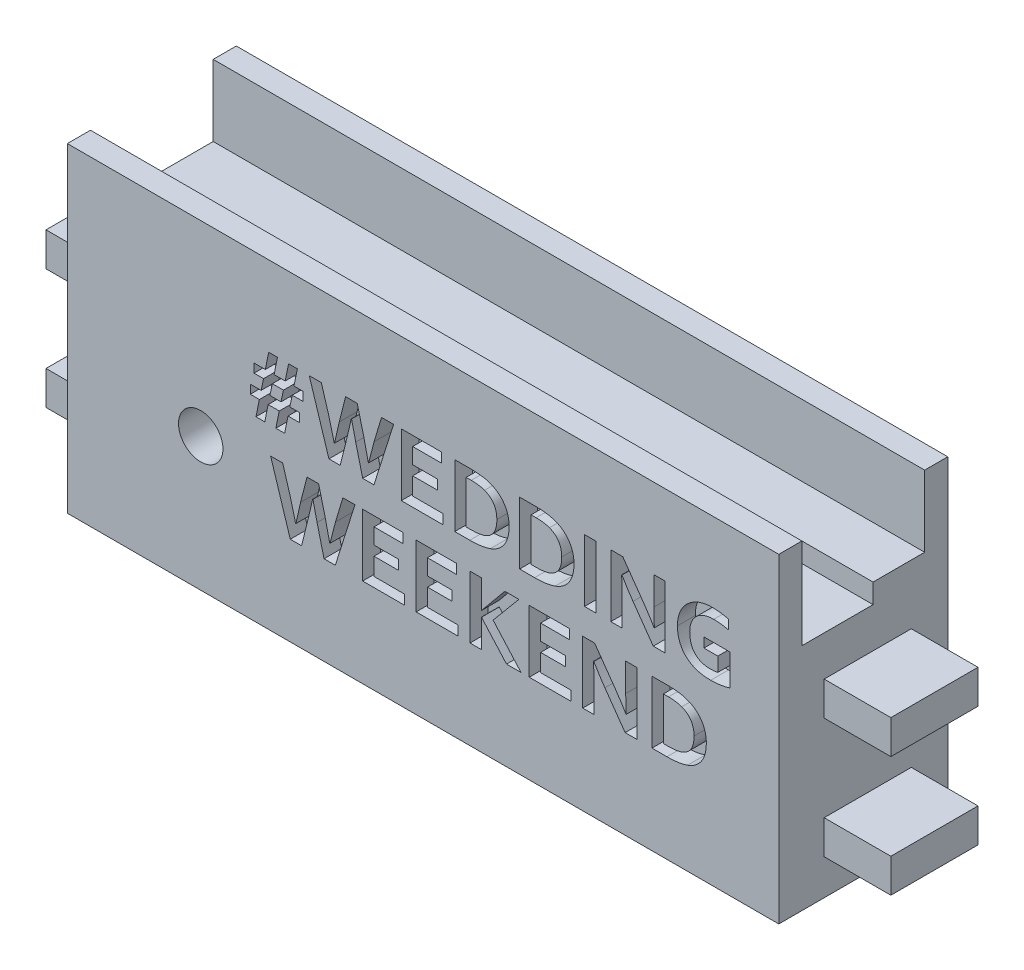
SolidWorks part; units mm, degrees
material "Copper"
ref_plane "Front Plane" through (0, 0, 0) normal (0, 0, 1) x (1, 0, 0)
ref_plane "Top Plane" through (0, 0, 0) normal (0, 1, 0) x (1, 0, 0)
ref_plane "Right Plane" through (0, 0, 0) normal (1, 0, 0) x (0, 0, -1)
sketch "Sketch1" plane through (0, 0, 0) normal (0, 0, 1) x (1, 0, 0)
  line L13 (0, 0) -> (101.6, 0)
  line L14 (0, 0) -> (0, 35.56)
  line L15 (0, 35.56) -> (101.6, 35.56)
  line L16 (101.6, 0) -> (101.6, 35.56)
  dimension "D1" = 35.56
  dimension "D2" = 101.6
extrude "Base Extrude" add sketch "Sketch1" along normal blind 24.13 contours L15 L16 L13 L14
sketch "Sketch2" plane through (101.6, 0, 0) normal (1, 0, 0) x (0, 0, -1)
  line L5 (-24.13, 0) -> (-24.13, 35.56) construction
  line L6 (-24.13, 35.56) -> (0, 35.56) construction
  line L14 (-11.43, 35.56) -> (-11.43, 0) construction
  line L15 (-24.13, 0) -> (0, 0) construction
  line L17 (-17.653, 9.906) -> (-5.207, 9.906)
  line L18 (-17.653, 9.906) -> (-17.653, 5.08)
  line L19 (-17.653, 5.08) -> (-5.207, 5.08)
  line L20 (-5.207, 9.906) -> (-5.207, 5.08)
  line L21 (-17.653, 27.051) -> (-5.207, 27.051)
  line L22 (-17.653, 27.051) -> (-17.653, 22.225)
  line L23 (-17.653, 22.225) -> (-5.207, 22.225)
  line L24 (-5.207, 27.051) -> (-5.207, 22.225)
  dimension "D1" = 12.7
  dimension "D2" = 22.225
  dimension "D4" = 12.446
  dimension "D5" = 4.826
  dimension "D6" = 5.08
  dimension "D8" = 6.223
extrude "Peg Extrude" add sketch "Sketch2" along normal blind 9.525
ref_plane "Peg Mirror Plane" through (50.8, 0, 0) normal (1, 0, 0) x (0, 0, -1)
mirror "Peg Mirror" about plane through (50.8, 0, 0) normal (1, 0, 0) of "Peg Extrude"
sketch "Sketch3" plane through (0, 35.56, 0) normal (0, 1, 0) x (1, 0, 0)
  line L0 (101.6, -24.13) -> (101.6, 0) construction
  line L1 (101.6, -24.13) -> (0, -24.13)
  line L2 (101.6, -24.13) -> (101.6, -20.828)
  line L3 (101.6, -20.828) -> (0, -20.828)
  line L4 (0, -24.13) -> (0, -20.828)
  line L5 (0, -24.13) -> (101.6, -24.13) construction
  line L6 (0, -24.13) -> (0, 0) construction
  line L8 (101.6, 0) -> (0, 0)
  line L9 (101.6, 0) -> (101.6, -3.302)
  line L10 (101.6, -3.302) -> (0, -3.302)
  line L11 (0, 0) -> (0, -3.302)
  dimension "D1" = 17.526
extrude "Picture Extrude" add sketch "Sketch3" along normal blind 10.16
sketch "Sketch6" plane through (0, 0, 0) normal (0, 0, -1) x (-1, 0, 0)
  line L0 (0, 0) -> (-101.6, 0) construction
  line L1 (-88.9, 31.115) -> (-31.75, 31.115)
  line L2 (-88.9, 31.115) -> (-88.9, 3.175)
  line L3 (-88.9, 3.175) -> (-31.75, 3.175)
  line L4 (-31.75, 31.115) -> (-31.75, 3.175)
  line L5 (-101.6, 0) -> (-101.6, 45.72) construction
  line L7 (-25.4, 31.115) -> (-12.7, 31.115)
  line L8 (-25.4, 31.115) -> (-25.4, 3.175)
  line L9 (-25.4, 3.175) -> (-12.7, 3.175)
  line L10 (-12.7, 31.115) -> (-12.7, 3.175)
  dimension "D1" = 57.15
  dimension "D2" = 27.94
  dimension "D3" = 3.175
  dimension "D4" = 12.7
  dimension "D5" = 12.7
  dimension "D6" = 6.35
  dimension "D7" = 27.94
extrude "Electronics Cut" cut sketch "Sketch6" against normal blind 19.05
sketch "Sketch7" plane through (31.75, 0, 0) normal (1, 0, 0) x (0, 0, -1)
  line L0 (-19.05, 3.175) -> (0, 3.175) construction
  line L1 (-6.35, 31.115) -> (0, 31.115)
  line L2 (-6.35, 31.115) -> (-6.35, 3.175)
  line L3 (-6.35, 3.175) -> (0, 3.175)
  line L4 (0, 31.115) -> (0, 3.175)
  line L5 (-19.05, 31.115) -> (0, 31.115) construction
  line L6 (0, 3.175) -> (0, 31.115) construction
  dimension "D1" = 6.35
extrude "Battery Wire Cut" cut sketch "Sketch7" against normal blind 6.35
sketch "Sketch8" plane through (0, 0, 19.05) normal (0, 0, -1) x (-1, 0, 0)
  line L1 (-88.9, 3.175) -> (-31.75, 3.175) construction
  line L2 (-25.4, 3.175) -> (-25.4, 31.115) construction
  circle A0 centre (-19.05, 19.05) radius 3.175
  dimension "D1" = 6.35
  dimension "D2" = 6.35
  dimension "D3" = 15.875
extrude "Switch Cut" cut sketch "Sketch8" against normal up to next
sketch "Sketch9" plane through (0, 35.56, 0) normal (0, 1, 0) x (1, 0, 0)
  line L1 (8.89, -14.478) -> (12.7, -14.478)
  line L2 (8.89, -14.478) -> (8.89, -20.828)
  line L3 (8.89, -20.828) -> (12.7, -20.828)
  line L4 (12.7, -14.478) -> (12.7, -20.828)
  line L5 (0, -20.828) -> (0, -3.302) construction
  line L7 (101.6, -20.828) -> (0, -20.828) construction
  point P4 (0, 0)
  point P8 (0, 0)
  dimension "D1" = 6.35
  dimension "D2" = 3.81
  dimension "D3" = 8.89
extrude "LED Wire Cut" cut sketch "Sketch9" against normal blind 12.7
sketch "Sketch10" plane through (0, 0, 0) normal (0, 0, -1) x (-1, 0, 0)
  line L1 (-101.6, 22.86) -> (0, 22.86) construction
  line L2 (-101.6, 0) -> (-101.6, 45.72) construction
  line L3 (0, 0) -> (0, 45.72) construction
  line L4 (-50.8, 45.72) -> (-50.8, 0) construction
  line L5 (-101.6, 45.72) -> (0, 45.72) construction
  line L6 (0, 0) -> (-101.6, 0) construction
  circle A0 centre (-95.25, 22.86) radius 1.905
  circle A1 centre (-6.35, 22.86) radius 1.905
  dimension "D1" = 3.81
  dimension "D2" = 6.35
extrude "Back Plate Holes" cut sketch "Sketch10" against normal blind 19.05
sketch "Sketch11" plane through (0, 0, 24.13) normal (0, 0, 1) x (1, 0, 0)
  line L0 (25.4, 25.4) -> (95.25, 25.4) construction
  line L1 (0, 0) -> (101.6, 0) construction
  line L2 (101.6, 0) -> (101.6, 45.72) construction
  line L3 (25.4, 12.7) -> (95.25, 12.7) construction
  text T0 "#WEDDING" font "Corbel" height 8.89
  text T1 "WEEKEND" font "Corbel" height 8.89
  dimension "D1" = 69.85
  dimension "D2" = 25.4
  dimension "D3" = 6.35
  dimension "D4" = 12.7
extrude "Text Cut" cut sketch "Sketch11" against normal blind 2.54
sketch "Sketch12" plane through (0, 35.56, 0) normal (0, 1, 0) x (1, 0, 0)
  line L1 (101.6, -20.828) -> (0, -20.828)
  line L2 (101.6, -20.828) -> (101.6, -10.668)
  line L3 (101.6, -10.668) -> (0, -10.668)
  line L4 (0, -20.828) -> (0, -10.668)
  point P5 (50.8, -20.828)
  dimension "D1" = 10.16
  dimension "D2" = 101.6
extrude "LED Cut" cut sketch "Sketch12" against normal blind 2.794 contours L3 L4 L1 L2
